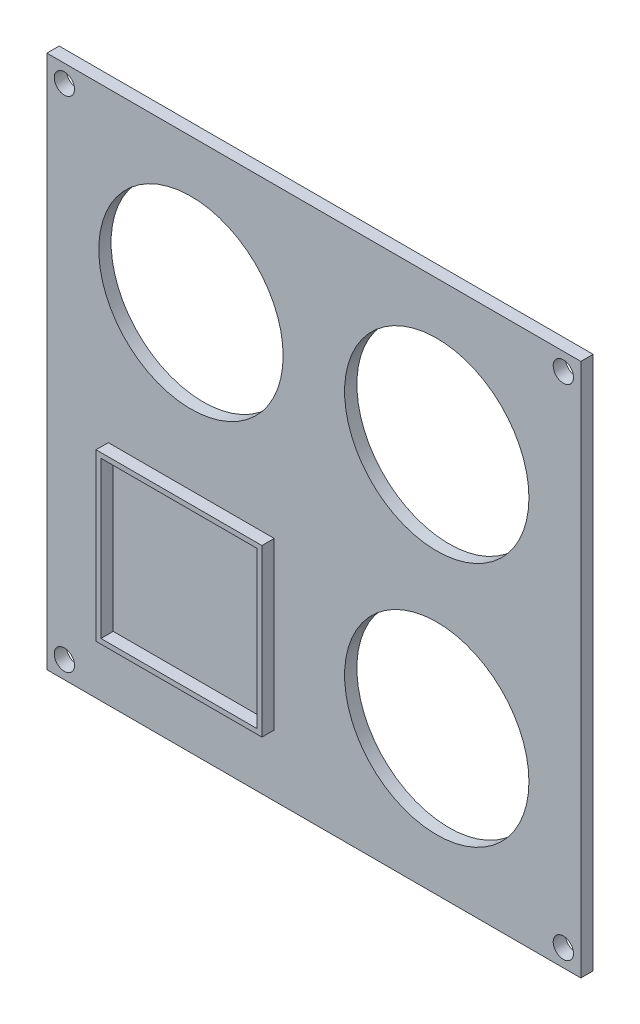
SolidWorks part; units mm, degrees
ref_plane "Front Plane" through (0, 0, 0) normal (1, 0, 0) x (0, 1, 0)
ref_plane "Top Plane" through (0, 0, 0) normal (0, 0, 1) x (0, 1, 0)
ref_plane "Right Plane" through (0, 0, 0) normal (0, 1, 0) x (-1, 0, 0)
sketch "Sketch1" plane through (0, 0, 0) normal (0, 0, 1) x (0, 1, 0)
  line L1 (0, 0) -> (86.9, 0)
  line L2 (0, 0) -> (0, 86.9)
  line L3 (0, 86.9) -> (86.9, 86.9)
  line L4 (86.9, 0) -> (86.9, 86.9)
  dimension "D1" = 86.9
  dimension "D2" = 86.9
extrude "Boss-Extrude1" add sketch "Sketch1" along normal blind 2 contours L3 L4 L1 L2
sketch "Sketch2" plane through (0, 0, 2) normal (0, 0, 1) x (1, 0, 0)
  line L0 (0, 0) -> (-86.9, 0) construction
  line L1 (-84.05, 84.05) -> (-2.85, 84.05) construction
  line L2 (-84.05, 84.05) -> (-84.05, 2.85) construction
  line L3 (-84.05, 2.85) -> (-2.85, 2.85) construction
  line L4 (-2.85, 84.05) -> (-2.85, 2.85) construction
  line L5 (0, 0) -> (0, 86.9) construction
  circle A0 centre (-84.05, 2.85) radius 1.65
  circle A1 centre (-2.85, 2.85) radius 1.65
  circle A2 centre (-2.85, 84.05) radius 1.65
  circle A3 centre (-84.05, 84.05) radius 1.65
  dimension "D3" = 3.3
  dimension "D1" = 81.2
  dimension "D2" = 81.2
  dimension "D4" = 2.85
  dimension "D5" = 2.85
extrude "Cut-Extrude3" cut sketch "Sketch2" against normal through all
sketch "Sketch3" plane through (0, 0, 2) normal (0, 0, 1) x (1, 0, 0)
  line L0 (-86.9, 0) -> (-86.9, 86.9) construction
  line L1 (-76.9, 10) -> (-49.9, 10)
  line L2 (-76.9, 10) -> (-76.9, 37)
  line L3 (-76.9, 37) -> (-49.9, 37)
  line L4 (-49.9, 10) -> (-49.9, 37)
  line L5 (0, 0) -> (-86.9, 0) construction
  dimension "D1" = 27
  dimension "D2" = 27
  dimension "D3" = 10
  dimension "D4" = 10
extrude "Boss-Extrude2" add sketch "Sketch3" along normal blind 2
sketch "Sketch4" plane through (0, 0, 4) normal (0, 0, 1) x (1, 0, 0)
  line L1 (-76.1, 36.2) -> (-50.7, 36.2)
  line L2 (-76.1, 36.2) -> (-76.1, 10.8)
  line L3 (-76.1, 10.8) -> (-50.7, 10.8)
  line L4 (-50.7, 36.2) -> (-50.7, 10.8)
  line L5 (-76.9, 37) -> (-49.9, 10) construction
  line L6 (-76.1, 10.8) -> (-50.7, 36.2) construction
  point P8 (-63.4, 23.5)
  point P9 (-63.4, 23.5)
  dimension "D1" = 25.4
  dimension "D2" = 25.4
extrude "Cut-Extrude4" cut sketch "Sketch4" against normal blind 2
sketch "Sketch5" plane through (0, 0, 2) normal (0, 0, 1) x (1, 0, 0)
  line L0 (-86.9, 86.9) -> (0, 0) construction
  line L1 (-86.9, 0) -> (0, 86.9) construction
  line L2 (-63.45, 63.45) -> (-23.45, 63.45) construction
  line L3 (-23.45, 63.45) -> (-23.45, 23.45) construction
  circle A0 centre (-63.45, 63.45) radius 15
  circle A1 centre (-23.45, 63.45) radius 15
  circle A2 centre (-23.45, 23.45) radius 15
  dimension "D1" = 30
  dimension "D2" = 40
extrude "Cut-Extrude5" cut sketch "Sketch5" against normal blind 2
